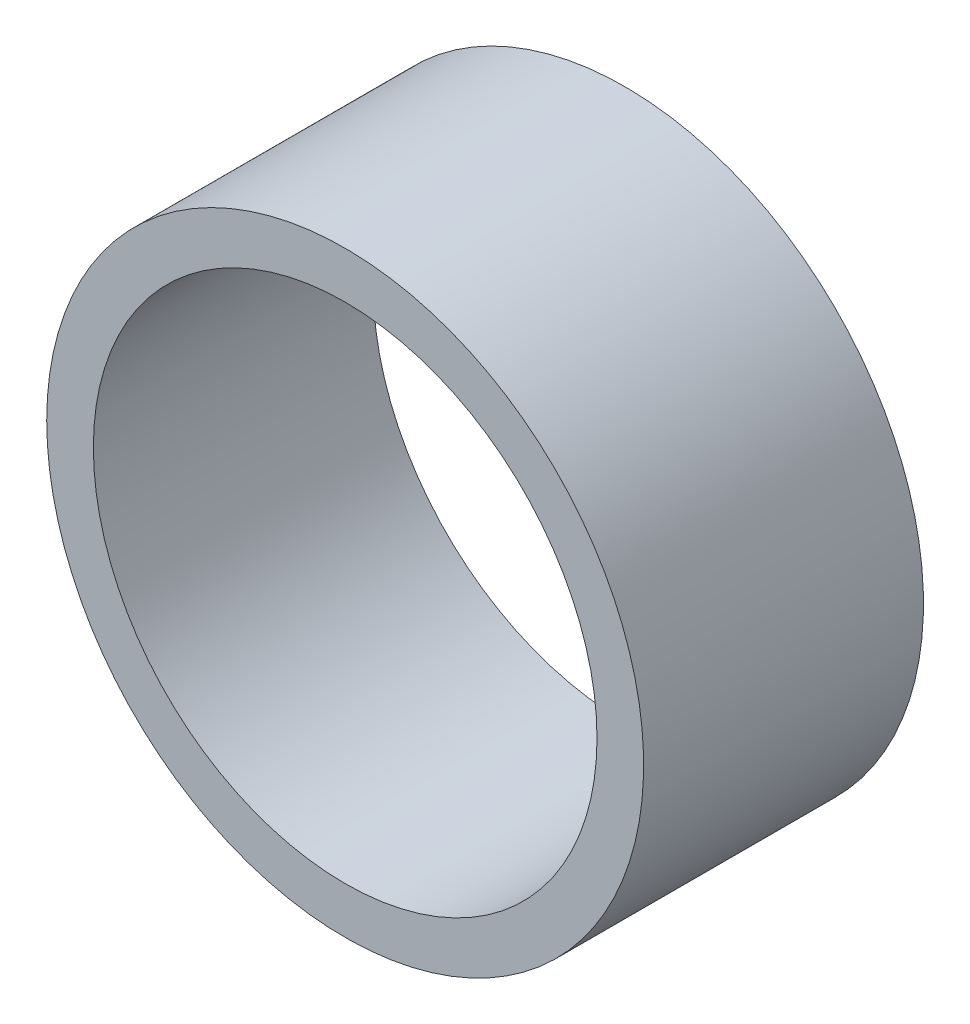
SolidWorks part; units mm, degrees
material "AISI 304"
ref_plane "Front Plane" through (0, 0, 0) normal (0, 0, 1) x (1, 0, 0)
ref_plane "Top Plane" through (0, 0, 0) normal (0, 1, 0) x (1, 0, 0)
ref_plane "Right Plane" through (0, 0, 0) normal (1, 0, 0) x (0, 0, -1)
sketch "Sketch1" plane through (0, 0, 0) normal (0, 0, 1) x (1, 0, 0)
  circle A0 centre (0, 0) radius 2.7
  circle A1 centre (0, 0) radius 3.2
  dimension "D1" = 5.4
  dimension "D2" = 0.5
extrude "Boss-Extrude1" add sketch "Sketch1" along normal blind 3
